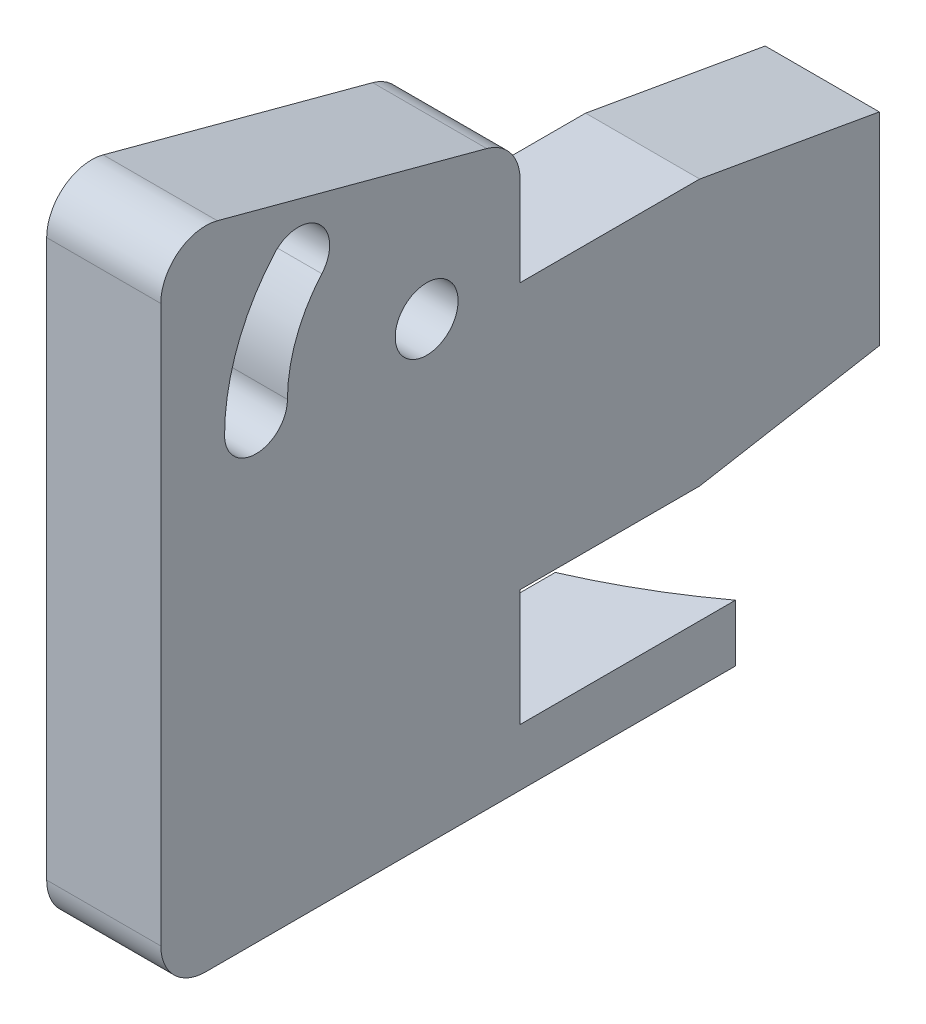
SolidWorks part; units mm, degrees
material "ABS"
ref_plane "Front Plane" through (0, 0, 0) normal (0, 0, 1) x (1, 0, 0)
ref_plane "Top Plane" through (0, 0, 0) normal (0, 1, 0) x (1, 0, 0)
ref_plane "Right Plane" through (0, 0, 0) normal (1, 0, 0) x (0, 0, -1)
sketch "Sketch1" plane through (0, 0, 0) normal (1, 0, 0) x (0, 0, -1)
  line L1 (-20, 19.4375) -> (20, 19.4375)
  line L2 (-20, 19.4375) -> (-20, -19.4375)
  line L3 (-20, -19.4375) -> (20, -19.4375)
  line L4 (20, 19.4375) -> (20, -19.4375)
  line L5 (20, -16.2625) -> (0, -16.2625)
  line L6 (20, -16.2625) -> (20, -9.7625)
  line L7 (20, -9.7625) -> (0, -9.7625)
  line L8 (0, -16.2625) -> (0, -9.7625)
  line L9 (20, 5.0375) -> (0, 5.0375)
  line L10 (20, 5.0375) -> (20, 11.5375)
  line L11 (20, 11.5375) -> (0, 11.5375)
  line L12 (0, 5.0375) -> (0, 11.5375)
  line L13 (0, 11.5375) -> (20, 11.5375)
  line L14 (0, 11.5375) -> (0, 19.4375)
  line L15 (0, 19.4375) -> (20, 19.4375)
  line L16 (20, 11.5375) -> (20, 19.4375)
  point P12 (-20, 0)
  dimension "D1" = 3.175
  dimension "D2" = 6.5
  dimension "D3" = 27.8
  dimension "D4" = 6.5
  dimension "D5" = 40
  dimension "D6" = 20
  dimension "D7" = 38.875
extrude "Boss-Extrude1" add sketch "Sketch1" along normal blind 6.353 contours L9 L12 L11 L4 L1 L2 L3 L5 L8 L7
sketch "Sketch2" plane through (6.353, 0, 0) normal (1, 0, 0) x (0, 0, -1)
  line L0 (-20, 19.4375) -> (0, 19.4375) construction
  line L1 (-20, 19.4375) -> (-20, -19.4375) construction
  line L2 (0, 5.0375) -> (0, 19.4375) construction
  line L3 (-20, 19.4375) -> (0, 19.4375)
  line L4 (-20, 19.4375) -> (-20, 17.2965)
  line L5 (-20, 17.2965) -> (0, 11.9375)
  line L6 (0, 19.4375) -> (0, 11.9375)
  circle A0 centre (-14.7, 5.8875) radius 1.75
  circle A1 centre (-5.2, 5.8875) radius 1.75
  arc A2 (-14.7, 5.8875) -> (-12.3513, 12.1412) centre (-5.2, 5.8875) cw construction
  arc A3 (-13.6687, 13.2932) -> (-16.45, 5.8875) centre (-5.2, 5.8875) ccw
  arc A4 (-11.034, 10.9892) -> (-12.95, 5.8875) centre (-5.2, 5.8875) ccw
  arc A5 (-11.034, 10.9892) -> (-13.6687, 13.2932) centre (-12.3513, 12.1412) ccw
  arc A6 (-16.45, 5.8875) -> (-12.95, 5.8875) centre (-14.7, 5.8875) ccw
  point P16 (-14.0935, 9.2276)
  point P21 (-14.3187, 8.5519)
  point P22 (0, 0)
  point P23 (-20, 15.0514)
  point P24 (-12.2759, 12.2264)
  line M2 (0, 5.0375) -> (0, 19.4375)
  line M5 (0, 19.4375) -> (-20, 19.4375)
  line M6 (-20, 19.4375) -> (-20, -19.4375)
  dimension "D2" = 3.5
  dimension "D6" = 1.75
  dimension "D8" = 15
  dimension "D1" = 13.55
  dimension "D3" = 9.5
  dimension "D4" = 5.3
  dimension "D5" = 7.5
  dimension "D7" = 3
extrude "Cut-Extrude1" cut sketch "Sketch2" against normal up to next contours A4 A5 A3 A0 | A0 | A1 | L5 M6 M2 M5
sketch "Sketch3" plane through (0, -19.4375, 0) normal (0, -1, 0) x (1, 0, 0)
  line L0 (6.353, 20) -> (0, 20) construction
  circle A0 centre (-13, -38.1) radius 32.5
  dimension "D3" = 65
  dimension "D1" = 13
  dimension "D2" = 58.1
extrude "Cut-Extrude2" cut sketch "Sketch3" against normal up to surface (9.675 mm away) up to face at (3.1765, -9.7625, -10)
fillet "Fillet1" radius 2.5 3 edges at (3.1765, 11.9375, 0) (3.1765, -19.4375, 20) (3.1765, 17.2965, 20)
chamfer "Chamfer1" distance 10 angle 10 1 edges at (3.1765, 5.0375, -20)
chamfer "Chamfer2" distance 10 angle 10 1 edges at (3.1765, -9.7625, -20)
